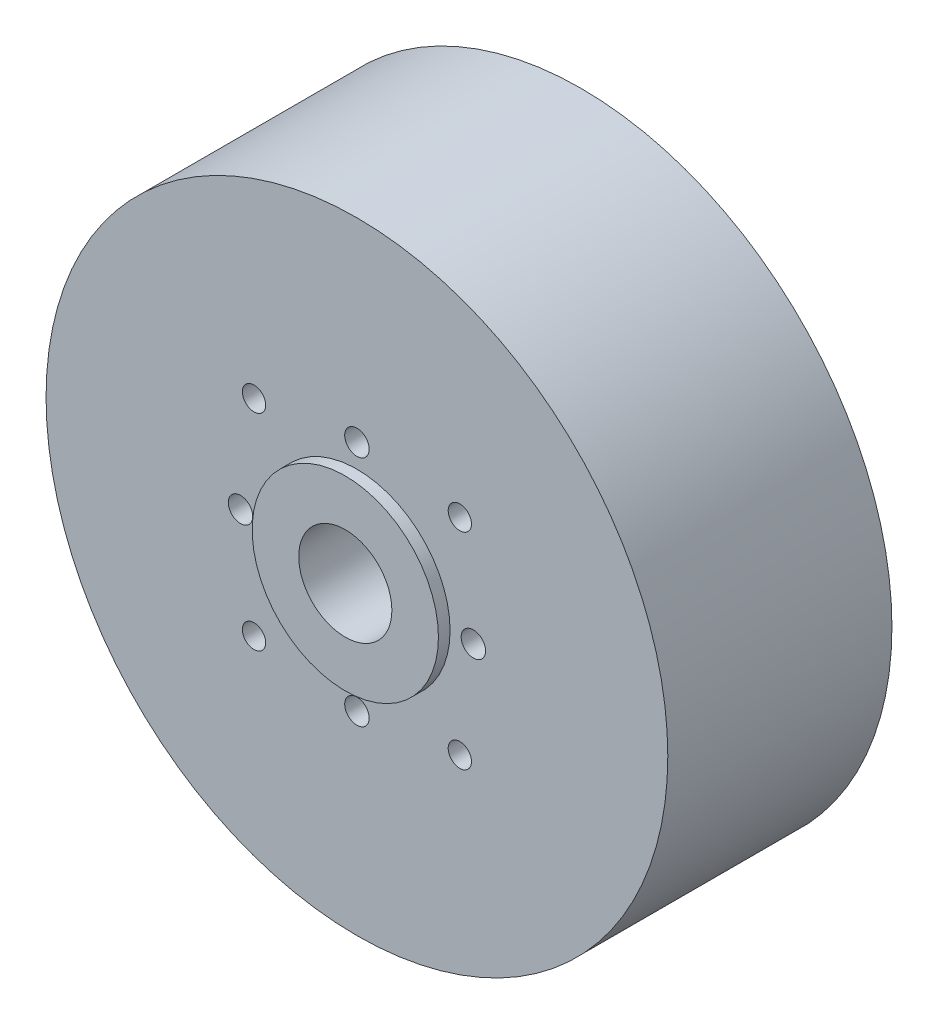
SolidWorks part; units mm, degrees
ref_plane "Front Plane" through (0, 0, 0) normal (0, 0, 1) x (1, 0, 0)
ref_plane "Top Plane" through (0, 0, 0) normal (0, 1, 0) x (1, 0, 0)
ref_plane "Right Plane" through (0, 0, 0) normal (1, 0, 0) x (0, 0, -1)
sketch "Sketch3" plane through (0, 0, 0) normal (0, 0, 1) x (1, 0, 0)
  circle A0 centre (0, 0) radius 53.4
  dimension "D1" = 106.8
extrude "Boss-Extrude1" add sketch "Sketch3" against normal blind 38.5
sketch "Sketch4" plane through (0, 0, 0) normal (0, 0, 1) x (1, 0, 0)
  circle A0 centre (0, 0) radius 8
  dimension "D1" = 16
extrude "Cut-Extrude1" cut sketch "Sketch4" against normal through all
sketch "Sketch5" plane through (0, 0, 0) normal (0, 0, 1) x (1, 0, 0)
  line L0 (0, 0) -> (-17.6777, 17.6777) construction
  line L1 (0, 0) -> (0, 25) construction
  line L2 (0, 0) -> (17.6777, -17.6777) construction
  line L3 (0, 0) -> (17.6777, 17.6777) construction
  line L4 (0, 0) -> (-17.6777, -17.6777) construction
  arc A0 (-19.0342, -16.208) -> (-16.208, -19.0342) centre (0, 0) ccw
  circle A1 centre (-17.6777, 17.6777) radius 2
  circle A2 centre (17.6777, 17.6777) radius 2
  circle A3 centre (-17.6777, -17.6777) radius 2
  circle A4 centre (17.6777, -17.6777) radius 2
  dimension "D1" = 50
  dimension "D4" = 4
  dimension "D5" = 4
  dimension "D6" = 4
  dimension "D7" = 4
  dimension "D2" = 45
  dimension "D3" = 45
extrude "Cut-Extrude2" cut sketch "Sketch5" against normal blind 20 contours A4 | A2 | A1 | A3
sketch "Sketch6" plane through (0, 0, 0) normal (0, 0, 1) x (1, 0, 0)
  circle A0 centre (0, 0) radius 16
  circle A1 centre (0, 0) radius 8
  dimension "D1" = 32
  dimension "D2" = 16
extrude "Boss-Extrude3" add sketch "Sketch6" along normal blind 2
sketch "Sketch7" plane through (0, 0, 0) normal (0, 0, 1) x (1, 0, 0)
  line L0 (0, 0) -> (20, 0) construction
  line L1 (0, 0) -> (0, 20) construction
  arc A0 (-19.8898, 2.0971) -> (-19.8898, -2.0971) centre (0, 0) ccw
  circle A1 centre (0, 20) radius 2.1
  circle A2 centre (20, 0) radius 2.1
  circle A3 centre (-20, 0) radius 2.1
  circle A4 centre (0, -20) radius 2.1
  arc A5 (-2.0971, -19.8898) -> (2.0971, -19.8898) centre (0, 0) ccw
  arc A6 (19.8898, -2.0971) -> (19.8898, 2.0971) centre (0, 0) ccw
  arc A7 (2.0971, 19.8898) -> (-2.0971, 19.8898) centre (0, 0) ccw
  dimension "D1" = 40
  dimension "D2" = 4.2
  dimension "D3" = 4.2
  dimension "D4" = 4.2
  dimension "D5" = 4.2
extrude "Cut-Extrude3" cut sketch "Sketch7" against normal blind 20 contours A4 | A2 | A1 | A3
sketch "Sketch8" plane through (0, 0, -38.5) normal (0, 0, -1) x (-1, 0, 0)
  line L0 (0, 27.5) -> (0, 30) construction
  line L1 (0, 0) -> (0, -30) construction
  line L2 (27.5, 0) -> (30, 0) construction
  line L3 (0, 0) -> (-30, 0) construction
  arc A0 (-29.8958, 2.4978) -> (-29.8958, -2.4978) centre (0, 0) ccw
  circle A1 centre (0, 30) radius 2.5
  circle A2 centre (30, 0) radius 2.5
  circle A3 centre (0, -30) radius 2.5
  circle A4 centre (-30, 0) radius 2.5
  arc A5 (2.4978, 29.8958) -> (-2.4978, 29.8958) centre (0, 0) ccw
  arc A6 (29.8958, -2.4978) -> (29.8958, 2.4978) centre (0, 0) ccw
  arc A7 (-2.4978, -29.8958) -> (2.4978, -29.8958) centre (0, 0) ccw
  dimension "D1" = 60
  dimension "D2" = 5
  dimension "D3" = 5
  dimension "D4" = 5
  dimension "D5" = 5
extrude "Cut-Extrude4" cut sketch "Sketch8" against normal blind 20 contours A4 | A1 | A2 | A3
